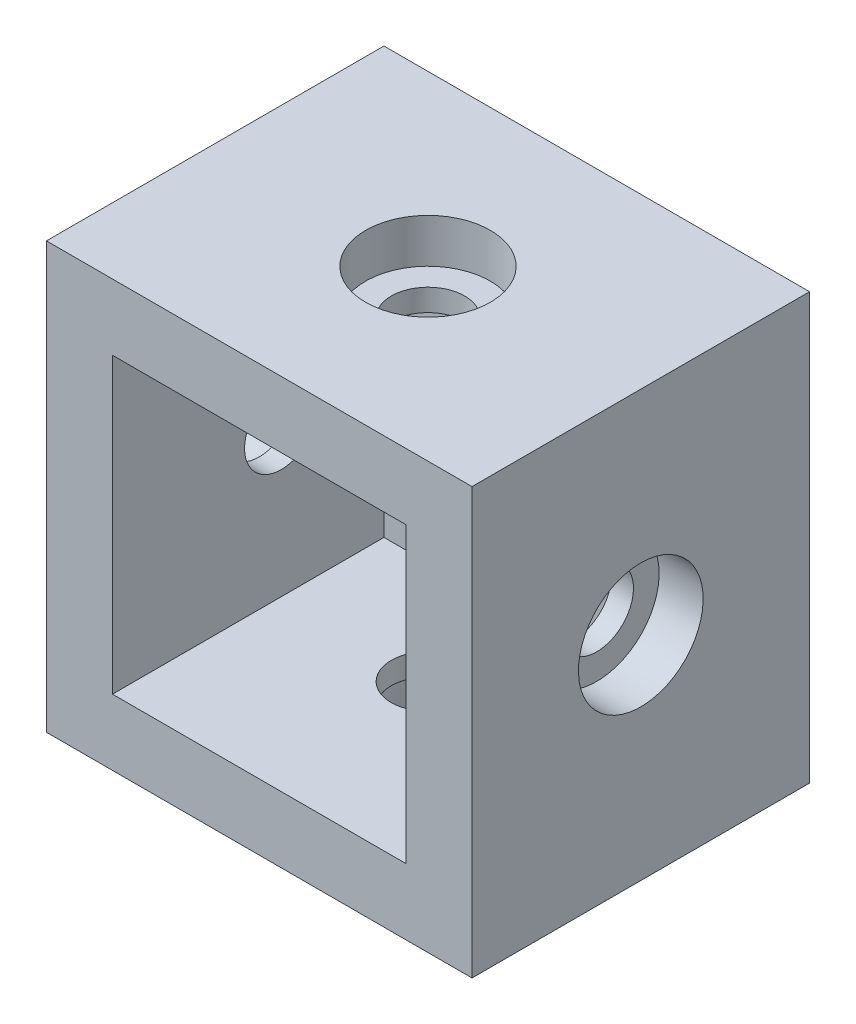
SolidWorks part; units mm, degrees
ref_plane "Front Plane" through (0, 0, 0) normal (0, 0, 1) x (1, 0, 0)
ref_plane "Top Plane" through (0, 0, 0) normal (0, 1, 0) x (1, 0, 0)
ref_plane "Right Plane" through (0, 0, 0) normal (1, 0, 0) x (0, 0, -1)
sketch "Sketch2" plane through (0, 0, 0) normal (0, 0, 1) x (1, 0, 0)
  line L1 (-11.6377, 12.0164) -> (17.3623, 12.0164)
  line L2 (-11.6377, 12.0164) -> (-11.6377, -16.9836)
  line L3 (-11.6377, -16.9836) -> (17.3623, -16.9836)
  line L4 (17.3623, 12.0164) -> (17.3623, -16.9836)
  dimension "D1" = 29
  dimension "D2" = 29
extrude "Boss-Extrude3" add sketch "Sketch2" along normal blind 23
sketch "Sketch5" plane through (0, 0, 23) normal (0, 0, 1) x (1, 0, 0)
  line L6 (17.3623, 12.0164) -> (-11.6377, 12.0164) construction
  line L7 (-7.1377, 7.5164) -> (12.8623, 7.5164)
  line L8 (-7.1377, 7.5164) -> (-7.1377, -12.4836)
  line L9 (-7.1377, -12.4836) -> (12.8623, -12.4836)
  line L10 (12.8623, 7.5164) -> (12.8623, -12.4836)
  line L11 (17.3623, -16.9836) -> (17.3623, 12.0164) construction
  dimension "D1" = 20
  dimension "D2" = 20
  dimension "D3" = 4.5
  dimension "D4" = 4.5
shell "Shell3" thickness 4.5
sketch "Sketch7" plane through (0, -16.9836, 0) normal (0, -1, 0) x (-1, 0, 0)
  line L0 (11.6377, -23) -> (-17.3623, -23) construction
  line L1 (-2.8623, -23) -> (-2.8623, 0) construction
  line L3 (11.6377, 0) -> (-17.3623, 0) construction
  line L4 (11.6377, -11.5) -> (-17.3623, -11.5) construction
  line L5 (11.6377, -23) -> (11.6377, 0) construction
  line L6 (-17.3623, -23) -> (-17.3623, 0) construction
  circle A0 centre (-2.8623, -11.5) radius 4.25
  point P16 (-2.8623, -11.5)
  dimension "D1" = 8.5
sketch "Sketch8" plane through (-11.6377, 0, 0) normal (-1, 0, 0) x (0, 0, 1)
  line L0 (0, -2.4836) -> (23, -2.4836) construction
  line L1 (23, 12.0164) -> (23, -16.9836) construction
  line L2 (11.5, -16.9836) -> (11.5, 12.0164) construction
  line L3 (23, -16.9836) -> (0, -16.9836) construction
  line L4 (23, 12.0164) -> (0, 12.0164) construction
  line L5 (0, 12.0164) -> (0, -16.9836) construction
  circle A0 centre (11.5, -2.4836) radius 4.25
  point P13 (0, 0)
  point P14 (23, -2.6807)
  point P15 (0, 0)
  point P16 (0, -2.4836)
  point P19 (23, -2.4836)
  point P20 (11.5, 12.0164)
  point P21 (11.5, -2.4836)
  dimension "D1" = 8.5
sketch "Sketch9" plane through (0, 12.0164, 0) normal (0, 1, 0) x (1, 0, 0)
  line L0 (-11.6377, -11.5) -> (17.3623, -11.5) construction
  line L1 (-11.6377, -23) -> (-11.6377, 0) construction
  line L2 (17.3623, -23) -> (17.3623, 0) construction
  line L3 (2.8623, 0) -> (2.8623, -23) construction
  line L4 (17.3623, 0) -> (-11.6377, 0) construction
  line L5 (17.3623, -23) -> (-11.6377, -23) construction
  circle A0 centre (2.8623, -11.5) radius 4.25
  dimension "D1" = 8.5
sketch "Sketch10" plane through (17.3623, 0, 0) normal (1, 0, 0) x (0, 0, -1)
  line L0 (-11.5, 12.0164) -> (-11.5, -16.9836) construction
  line L1 (0, -2.4836) -> (-23, -2.4836) construction
  line L2 (0, -16.9836) -> (0, 12.0164) construction
  line L3 (-23, -16.9836) -> (-23, 12.0164) construction
  circle A0 centre (-11.5, -2.4836) radius 4.25
  point P6 (-11.3394, -2.4836)
  point P7 (0, -2.4836)
  dimension "D1" = 8.5
extrude "Cut-Extrude9" cut sketch "Sketch7" against normal blind 3 contours A0
extrude "Cut-Extrude10" cut sketch "Sketch10" against normal blind 3 contours A0
extrude "Cut-Extrude11" cut sketch "Sketch9" against normal blind 3 contours A0
extrude "Cut-Extrude12" cut sketch "Sketch8" against normal blind 3 contours A0
sketch "Sketch12" plane through (0, 9.0164, 0) normal (0, 1, 0) x (1, 0, 0)
  circle A0 centre (2.8623, -11.5) radius 2.5
  dimension "D1" = 5
sketch "Sketch13" plane through (14.3623, 0, 0) normal (1, 0, 0) x (0, 0, -1)
  circle A0 centre (-11.5, -2.4836) radius 2.5
  dimension "D1" = 5
extrude "Cut-Extrude13" cut sketch "Sketch12" against normal through all contours A0
extrude "Cut-Extrude14" cut sketch "Sketch13" against normal blind 11.5 contours A0
sketch "Sketch14" plane through (-8.6377, 0, 0) normal (-1, 0, 0) x (0, 0, 1)
  circle A0 centre (11.5, -2.4836) radius 2.5
  dimension "D1" = 5
extrude "Cut-Extrude15" cut sketch "Sketch14" against normal blind 11.5
